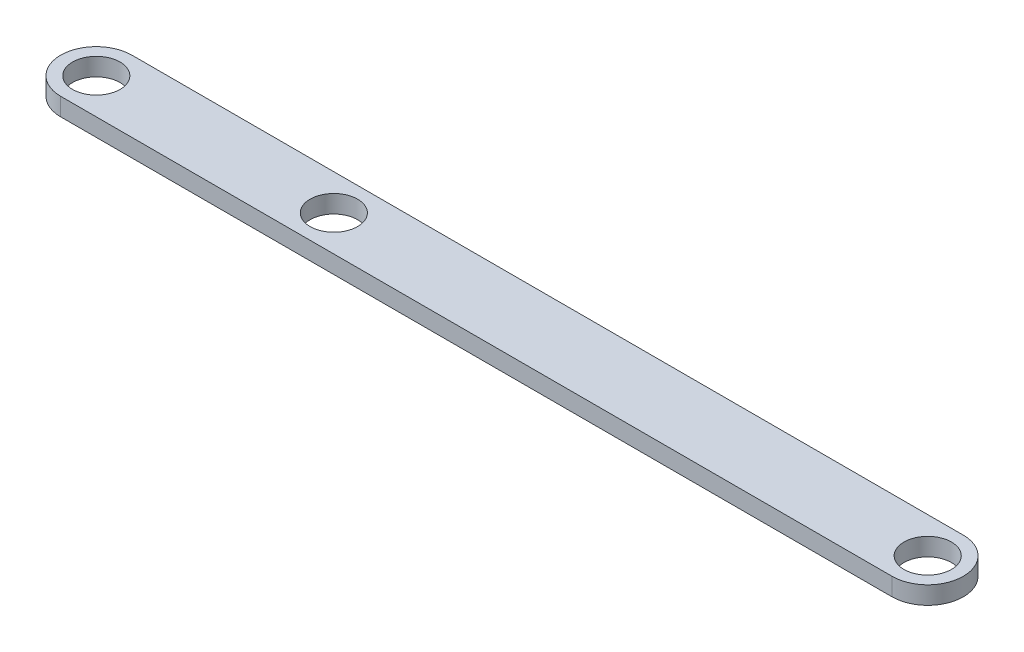
SolidWorks part; units mm, degrees
ref_plane "Front Plane" through (0, 0, 0) normal (0, 0, 1) x (1, 0, 0)
ref_plane "Top Plane" through (0, 0, 0) normal (0, 1, 0) x (1, 0, 0)
ref_plane "Right Plane" through (0, 0, 0) normal (1, 0, 0) x (0, 0, -1)
sketch "Sketch1" plane through (0, 0, 0) normal (0, 1, 0) x (1, 0, 0)
  line L0 (0, 6) -> (140, 6)
  line L1 (0, -6) -> (140, -6)
  circle A0 centre (0, 0) radius 4
  circle A1 centre (140, 0) radius 4
  arc A2 (0, 6) -> (0, -6) centre (0, 0) ccw
  arc A3 (140, -6) -> (140, 6) centre (140, 0) ccw
  circle A4 centre (0, 0) radius 6 construction
  circle A5 centre (140, 0) radius 6 construction
  dimension "D1" = 140
  dimension "D2" = 8
  dimension "D3" = 8
  dimension "D4" = 2
extrude "Boss-Extrude1" add sketch "Sketch1" along normal blind 3
sketch "Sketch2" plane through (0, 3, 0) normal (0, 1, 0) x (1, 0, 0)
  circle A0 centre (40, 0) radius 4
extrude "Cut-Extrude1" cut sketch "Sketch2" against normal through all
